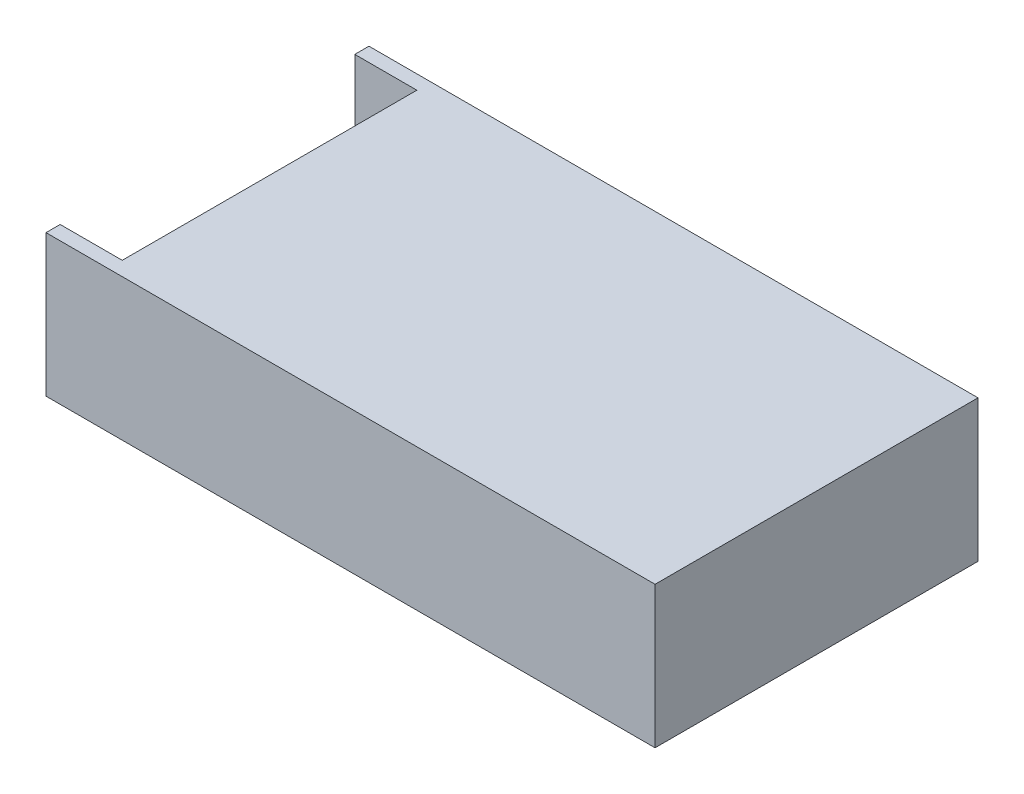
SolidWorks part; units mm, degrees
ref_plane "Plano frontal" through (0, 0, 0) normal (0, 0, 1) x (1, 0, 0)
ref_plane "Plano superior" through (0, 0, 0) normal (0, 1, 0) x (1, 0, 0)
ref_plane "Plano direito" through (0, 0, 0) normal (1, 0, 0) x (0, 0, -1)
sketch "Esboço1" plane through (0, 0, 0) normal (0, 1, 0) x (1, 0, 0)
  line L1 (-107.5, 57) -> (107.5, 57)
  line L2 (-107.5, 57) -> (-107.5, -57)
  line L3 (-107.5, -57) -> (107.5, -57)
  line L4 (107.5, 57) -> (107.5, -57)
  line L5 (-107.5, 57) -> (107.5, -57) construction
  line L6 (-107.5, -57) -> (107.5, 57) construction
  point P0 (0, 0)
  dimension "D1" = 215
  dimension "D2" = 114
extrude "Ressalto-extrusão1" add sketch "Esboço1" along normal blind 50
sketch "Esboço3" plane through (0, 0, 57) normal (0, 0, 1) x (1, 0, 0)
  line L1 (-107.5, 50) -> (-85.5852, 50)
  line L2 (-107.5, 50) -> (-107.5, 17.4571)
  line L3 (-102.4831, 16.1339) -> (-85.5852, 16.1339)
  line L4 (-85.5852, 50) -> (-85.5852, 16.1339)
  line L5 (-102.4831, 6.4269) -> (-107.5, 6.4269)
  line L6 (-102.4831, 6.4269) -> (-102.4831, 16.1339)
  line L8 (-107.5, 6.4269) -> (-107.5, 17.4571)
extrude "Corte-extrusão1" cut sketch "Esboço3" against normal offset from surface (104 mm away) 5 from offset 5 up to face at (0, 25, -57) offset against normal yes
sketch "Esboço4" plane through (0, 0, 0) normal (0, -1, 0) x (1, 0, 0)
  line L0 (107.5, 57) -> (107.5, -57) construction
  line L1 (-107.5, 57) -> (107.5, 57) construction
  circle A0 centre (96, 42) radius 2
  circle A1 centre (-29.6, 42) radius 2
  circle A2 centre (-29.6, -43) radius 2
  circle A3 centre (96, -43) radius 2
  point P8 (0, 0)
  point P9 (0, 0)
  point P10 (0, 0)
  point P11 (0, 0)
  dimension "D2" = 4
  dimension "D1" = 125.6
  dimension "D3" = 85
  dimension "D4" = 11.5
  dimension "D5" = 15
extrude "Corte-extrusão2" cut sketch "Esboço4" against normal blind 10
